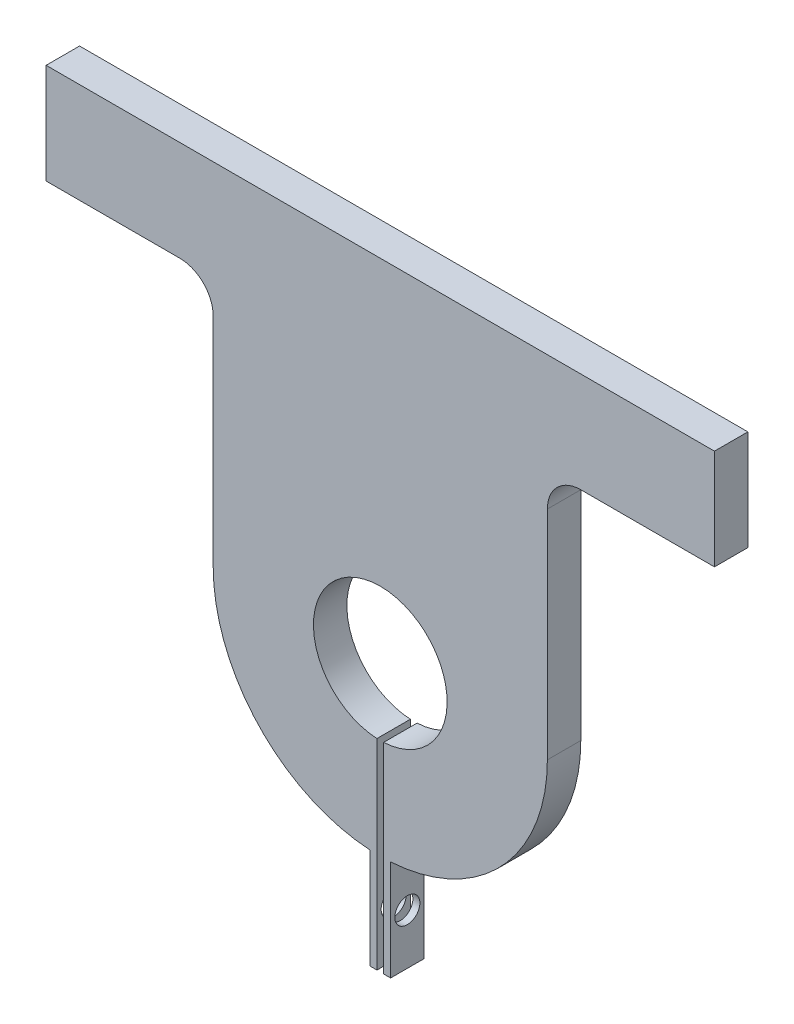
SolidWorks part; units mm, degrees
material "Plain Carbon Steel"
ref_plane "Front Plane" through (0, 0, 0) normal (0, 0, 1) x (1, 0, 0)
ref_plane "Top Plane" through (0, 0, 0) normal (0, 1, 0) x (1, 0, 0)
ref_plane "Right Plane" through (0, 0, 0) normal (1, 0, 0) x (0, 0, -1)
sketch "Sketch1" plane through (0, 0, 0) normal (0, 0, 1) x (1, 0, 0)
  line L0 (-25.4, 0) -> (-25.4, 33.02)
  line L1 (0, -10.16) -> (0, -25.4) construction
  line L2 (25.4, 33.02) -> (25.4, 0)
  line L3 (-30.48, 38.1) -> (-50.8, 38.1)
  line L4 (-50.8, 38.1) -> (-50.8, 53.34)
  line L5 (-50.8, 53.34) -> (50.8, 53.34)
  line L6 (50.8, 53.34) -> (50.8, 38.1)
  line L7 (50.8, 38.1) -> (30.48, 38.1)
  line L8 (0.508, -10.1473) -> (0.508, -25.3949)
  line L9 (-0.508, -10.1473) -> (-0.508, -25.3949)
  line L12 (-0.508, -25.3949) -> (-0.508, -40.6349)
  line L13 (-0.508, -40.6349) -> (-1.5741, -40.6349)
  line L14 (-1.5741, -40.6349) -> (-1.5741, -25.3512)
  line L15 (0.508, -25.3949) -> (0.508, -40.6349)
  line L16 (0.508, -40.6349) -> (1.5741, -40.6349)
  line L17 (1.5741, -40.6349) -> (1.5741, -25.3512)
  arc A0 (0.508, -10.1473) -> (-0.508, -10.1473) centre (0, 0) ccw
  arc A1 (-25.4, 0) -> (-1.5741, -25.3512) centre (0, 0) ccw
  arc A3 (25.4, 33.02) -> (30.48, 38.1) centre (30.48, 33.02) cw
  arc A4 (-25.4, 33.02) -> (-30.48, 38.1) centre (-30.48, 33.02) ccw
  arc A5 (1.5741, -25.3512) -> (25.4, 0) centre (0, 0) ccw
  point P7 (0, 53.34)
  dimension "D1" = 10.16
  dimension "D3" = 5.08
  dimension "D2" = 25.4
  dimension "D4" = 0.508
  dimension "D5" = 1.5741
  dimension "D6" = 50.8
  dimension "D7" = 38.1
extrude "Boss-Extrude1" add sketch "Sketch1" along normal blind 5.08
sketch "Sketch4" plane through (1.5741, 0, 0) normal (1, 0, 0) x (0, 0, -1)
  line L0 (0, -40.6349) -> (0, -25.3512) construction
  line L1 (-5.08, -25.3512) -> (0, -25.3512) construction
  circle A0 centre (-2.54, -32.9712) radius 1.905
  dimension "D1" = 3.81
  dimension "D2" = 2.54
  dimension "D3" = 7.62
extrude "Cut-Extrude2" cut sketch "Sketch4" against normal through all
ref_plane "Plane1" through (0, 0, 25.4) normal (0, 0, 1) x (1, 0, 0)
